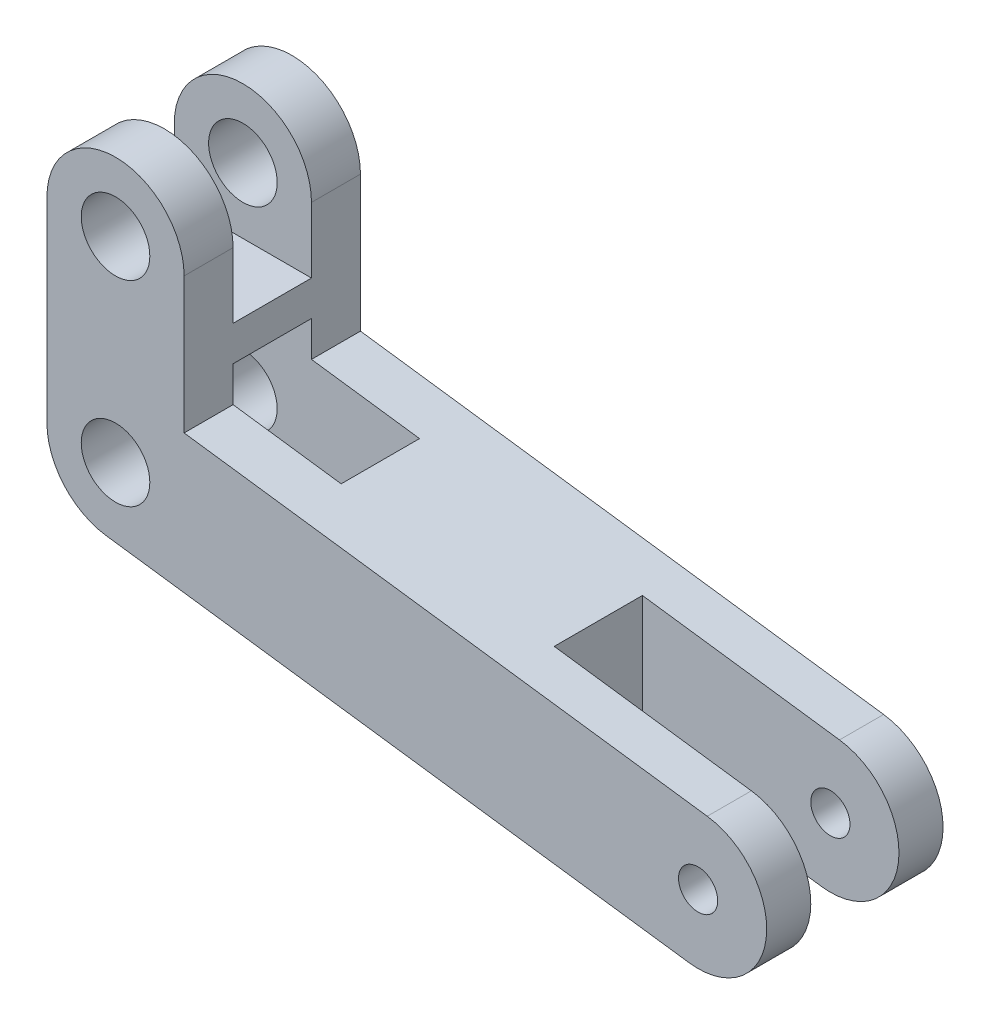
SolidWorks part; units mm, degrees
ref_plane "前视基准面" through (0, 0, 0) normal (0, 0, 1) x (1, 0, 0)
ref_plane "上视基准面" through (0, 0, 0) normal (0, 1, 0) x (1, 0, 0)
ref_plane "右视基准面" through (0, 0, 0) normal (1, 0, 0) x (0, 0, -1)
other "Configuration Table"
sketch "草图1" plane through (0, 0, 0) normal (0, 0, 1) x (1, 0, 0)
  line L0 (0, 10) -> (0, 1.75) construction
  line L1 (29.2655, -7.4687) -> (-0.4667, -3.4687)
  line L2 (-3.5, 10) -> (-3.5, 0)
  line L3 (3.5, 10) -> (3.5, 3.0607)
  line L8 (30.1988, -0.5313) -> (3.5, 3.0607)
  line L9 (29.7321, -3) -> (29.7321, -4) construction
  circle A0 centre (0, 0) radius 1.75
  arc A1 (-3.5, 0) -> (-0.4667, -3.4687) centre (0, 0) ccw
  arc A2 (3.5, 10) -> (-3.5, 10) centre (0, 10) ccw
  circle A4 centre (0, 10) radius 1.75
  arc A5 (29.2655, -7.4687) -> (30.1988, -0.5313) centre (29.7321, -4) ccw
  circle A6 centre (29.7321, -4) radius 1
  dimension "D1" = 10
  dimension "D2" = 3.5
  dimension "D3" = 7
  dimension "D8" = 2
  dimension "D4" = 30
  dimension "D5" = 4
extrude "凸台-拉伸1" add sketch "草图1" along normal mid plane 9
sketch "草图5" plane through (0, 0, 0) normal (0, 0, 1) x (1, 0, 0)
  line L1 (-5.6997, 16.4699) -> (3.5, 16.4699)
  line L2 (-5.6997, 16.4699) -> (-5.6997, 6.6567)
  line L3 (-5.6997, 6.6567) -> (3.5, 6.6567)
  line L4 (3.5, 16.4699) -> (3.5, 6.6567)
  line L5 (-5.6455, -5.6561) -> (9.0148, -5.6561)
  line L6 (-5.6455, -5.6561) -> (-5.6455, 4.8693)
  line L7 (-5.6455, 4.8693) -> (9.0148, 4.8693)
  line L8 (9.0148, -5.6561) -> (9.0148, 4.8693)
extrude "切除-拉伸3" cut sketch "草图5" against normal mid plane 4
sketch "草图6" plane through (0, 0, 0) normal (0, 0, 1) x (1, 0, 0)
  line L1 (39.3255, -10) -> (20.1387, -10)
  line L2 (39.3255, -10) -> (39.3255, 2)
  line L3 (39.3255, 2) -> (20.1387, 2)
  line L4 (20.1387, -10) -> (20.1387, 2)
  line L5 (39.3255, -10) -> (20.1387, 2) construction
  line L6 (39.3255, 2) -> (20.1387, -10) construction
  point P0 (29.7321, -4)
  dimension "D1" = 6
extrude "切除-拉伸4" cut sketch "草图6" against normal mid plane 4.5
